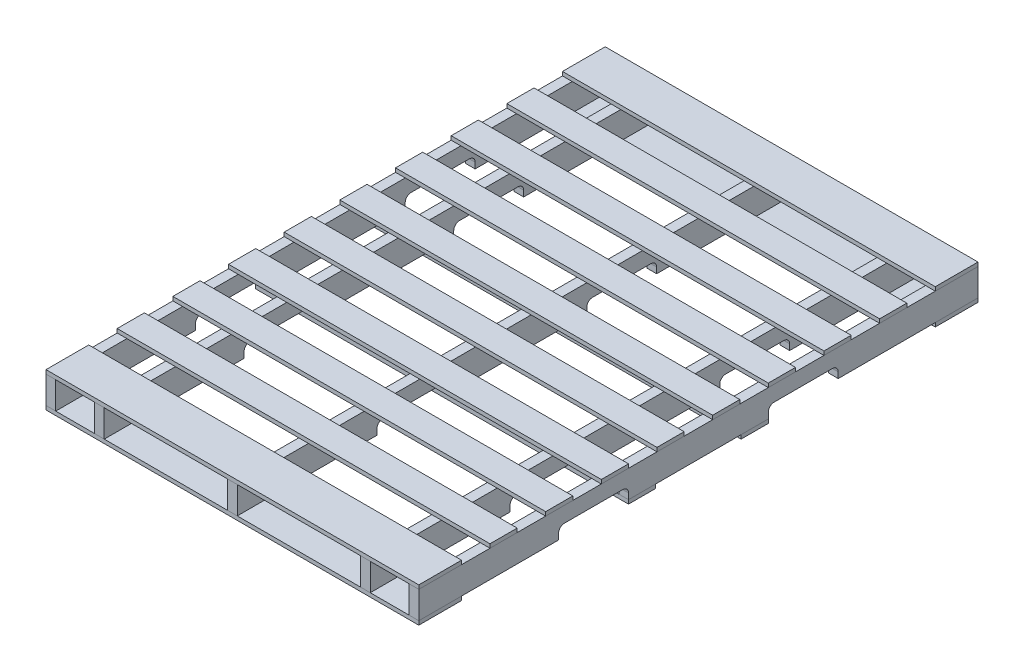
SolidWorks part; units mm, degrees
ref_plane "Front Plane" through (0, 0, 0) normal (0, 0, 1) x (1, 0, 0)
ref_plane "Top Plane" through (0, 0, 0) normal (0, 1, 0) x (1, 0, 0)
ref_plane "Right Plane" through (0, 0, 0) normal (1, 0, 0) x (0, 0, -1)
sketch "Sketch1" plane through (0, 0, 0) normal (0, 0, 1) x (1, 0, 0)
  line L0 (-609.6, 0) -> (609.6, 0) construction
  line L5 (-609.6, 57.15) -> (-609.6, -57.15) construction
  line L6 (609.6, 57.15) -> (609.6, -57.15) construction
  line L11 (-609.6, -57.15) -> (609.6, -57.15) construction
  line L12 (-609.6, 57.15) -> (609.6, 57.15) construction
  line L13 (-577.85, 57.15) -> (-577.85, -57.15) construction
  line L15 (-450.85, 57.15) -> (-450.85, -57.15) construction
  line L16 (-419.1, -57.15) -> (-419.1, 57.15) construction
  line L17 (0, 57.15) -> (0, -57.15) construction
  line L18 (-609.6, 0) -> (-577.85, 0)
  line L19 (-450.85, 0) -> (-419.1, 0)
  line L21 (577.85, 57.15) -> (577.85, -57.15) construction
  line L22 (-609.6, 44.45) -> (609.6, 44.45) construction
  line L23 (-609.6, -44.45) -> (609.6, -44.45) construction
  line L24 (419.1, 57.15) -> (450.85, 57.15)
  line L25 (419.1, 57.15) -> (419.1, -57.15)
  line L26 (419.1, -57.15) -> (450.85, -57.15)
  line L27 (450.85, 57.15) -> (450.85, -57.15)
  line L28 (-15.875, -57.15) -> (15.875, -57.15)
  line L29 (-15.875, -57.15) -> (-15.875, 57.15)
  line L30 (-15.875, 57.15) -> (15.875, 57.15)
  line L31 (15.875, -57.15) -> (15.875, 57.15)
  line L32 (-15.875, -57.15) -> (15.875, 57.15) construction
  line L33 (-15.875, 57.15) -> (15.875, -57.15) construction
  point P3 (0, 0)
  point P6 (-609.6, 0)
  point P9 (609.6, 0)
  point P23 (0, 0)
  point P32 (0, 0)
  dimension "D1" = 31.75
  dimension "Width" = 1219.2
  dimension "Height" = 114.3
  dimension "Maximum Fork Width" = 403.225
  dimension "D3" = 12.7
  dimension "Maximum Fork Height" = 88.9
sketch "Sketch2" plane through (0, 0, 0) normal (1, 0, 0) x (0, 0, -1)
  line L0 (914.4, 0) -> (-914.4, 0) construction
  point P4 (0, 0)
  dimension "Depth" = 1828.8
sketch "Sketch3" plane through (0, 0, 0) normal (0, 0, 1) x (1, 0, 0)
  line L0 (577.85, 57.15) -> (577.85, -57.15) construction
  line L5 (450.85, 57.15) -> (450.85, -57.15) construction
  line L6 (-577.85, 57.15) -> (-577.85, -57.15) construction
  line L7 (-609.6, 44.45) -> (-577.85, 44.45)
  line L8 (-609.6, 44.45) -> (-609.6, -44.45)
  line L9 (-609.6, -44.45) -> (-577.85, -44.45)
  line L10 (-577.85, 44.45) -> (-577.85, -44.45)
  line L11 (-609.6, 44.45) -> (609.6, 44.45) construction
  line L12 (450.85, 44.45) -> (419.1, 44.45)
  line L13 (-609.6, -44.45) -> (609.6, -44.45) construction
  line L14 (577.85, 44.45) -> (609.6, 44.45)
  line L15 (577.85, 44.45) -> (577.85, -44.45)
  line L16 (577.85, -44.45) -> (609.6, -44.45)
  line L17 (609.6, 44.45) -> (609.6, -44.45)
  line L18 (-609.6, 57.15) -> (-609.6, -57.15) construction
  line L19 (450.85, 44.45) -> (450.85, -44.45)
  line L20 (-450.85, 57.15) -> (-450.85, -57.15) construction
  line L21 (-450.85, 44.45) -> (-419.1, 44.45)
  line L22 (-450.85, 44.45) -> (-450.85, -44.45)
  line L23 (-450.85, -44.45) -> (-419.1, -44.45)
  line L24 (-419.1, 44.45) -> (-419.1, -44.45)
  line L25 (-419.1, -57.15) -> (-419.1, 57.15) construction
  line L26 (450.85, -44.45) -> (419.1, -44.45)
  line L27 (419.1, 44.45) -> (419.1, -44.45)
  line L28 (419.1, 57.15) -> (419.1, -57.15) construction
  line L29 (15.875, -57.15) -> (15.875, 57.15) construction
  line L30 (-15.875, -44.45) -> (15.875, -44.45)
  line L31 (-15.875, -44.45) -> (-15.875, 44.45)
  line L32 (-15.875, 44.45) -> (15.875, 44.45)
  line L33 (15.875, -44.45) -> (15.875, 44.45)
  line L34 (-15.875, -44.45) -> (15.875, 44.45) construction
  line L35 (-15.875, 44.45) -> (15.875, -44.45) construction
  point P35 (0, 0)
extrude "Boss-Extrude1" add sketch "Sketch3" along normal up to vertex (914.4 mm away) and the other way up to vertex (914.4 mm away) up to point (0, 0, 914.4) other way up to point (0, 0, -914.4)
sketch "Sketch4" plane through (0, 44.45, 0) normal (0, 1, 0) x (1, 0, 0)
  line L0 (609.6, -914.4) -> (609.6, 914.4) construction
  line L1 (-609.6, -914.4) -> (609.6, -914.4)
  line L2 (-609.6, -914.4) -> (-609.6, -774.7)
  line L3 (-609.6, -774.7) -> (609.6, -774.7)
  line L4 (609.6, -914.4) -> (609.6, -774.7)
  line L22 (-609.6, -914.4) -> (-609.6, 914.4) construction
  line L26 (-609.6, 774.7) -> (609.6, 774.7)
  line L27 (-609.6, 774.7) -> (-609.6, 914.4)
  line L28 (-609.6, 914.4) -> (609.6, 914.4)
  line L29 (609.6, 774.7) -> (609.6, 914.4)
  line L30 (609.6, 592.6667) -> (609.6, 499.5333) construction
  line L31 (-609.6, -681.5667) -> (609.6, -681.5667)
  line L32 (-609.6, -681.5667) -> (-609.6, -592.6667)
  line L33 (-609.6, -592.6667) -> (609.6, -592.6667)
  line L34 (609.6, -681.5667) -> (609.6, -592.6667)
  line L35 (-609.6, -499.5333) -> (609.6, -499.5333)
  line L36 (-609.6, -499.5333) -> (-609.6, -410.6333)
  line L37 (-609.6, -410.6333) -> (609.6, -410.6333)
  line L38 (609.6, -499.5333) -> (609.6, -410.6333)
  line L39 (-609.6, 681.5667) -> (609.6, 681.5667)
  line L40 (-609.6, 681.5667) -> (-609.6, 592.6667)
  line L41 (-609.6, 592.6667) -> (609.6, 592.6667)
  line L42 (609.6, 681.5667) -> (609.6, 592.6667)
  line L43 (-609.6, -46.5667) -> (609.6, -46.5667)
  line L44 (-609.6, -46.5667) -> (-609.6, -135.4667)
  line L45 (-609.6, -135.4667) -> (609.6, -135.4667)
  line L46 (609.6, -46.5667) -> (609.6, -135.4667)
  line L47 (-609.6, -228.6) -> (609.6, -228.6)
  line L48 (-609.6, -228.6) -> (-609.6, -317.5)
  line L49 (-609.6, -317.5) -> (609.6, -317.5)
  line L50 (609.6, -228.6) -> (609.6, -317.5)
  line L51 (609.6, 499.5333) -> (-609.6, 499.5333)
  line L52 (609.6, 499.5333) -> (609.6, 410.6333)
  line L53 (609.6, 410.6333) -> (-609.6, 410.6333)
  line L54 (-609.6, 499.5333) -> (-609.6, 410.6333)
  line L55 (609.6, 317.5) -> (-609.6, 317.5)
  line L56 (609.6, 317.5) -> (609.6, 228.6)
  line L57 (609.6, 228.6) -> (-609.6, 228.6)
  line L58 (-609.6, 317.5) -> (-609.6, 228.6)
  line L59 (609.6, 135.4667) -> (-609.6, 135.4667)
  line L60 (609.6, 135.4667) -> (609.6, 46.5667)
  line L61 (609.6, 46.5667) -> (-609.6, 46.5667)
  line L62 (-609.6, 135.4667) -> (-609.6, 46.5667)
  line L63 (609.6, 774.7) -> (609.6, 681.5667) construction
  line L64 (609.6, 410.6333) -> (609.6, 317.5) construction
  line L65 (609.6, 228.6) -> (609.6, 135.4667) construction
  line L66 (609.6, 46.5667) -> (609.6, -46.5667) construction
  line L67 (609.6, -135.4667) -> (609.6, -228.6) construction
  line L68 (609.6, -317.5) -> (609.6, -410.6333) construction
  line L69 (609.6, -499.5333) -> (609.6, -592.6667) construction
  line L70 (609.6, -681.5667) -> (609.6, -774.7) construction
  line L71 (609.6, 681.5667) -> (609.6, 774.7) construction
  dimension "D1" = 139.7
  dimension "D3" = 88.9
extrude "Boss-Extrude2" add sketch "Sketch4" along normal up to vertex (12.7 mm away) separate body up to point (-609.6, 57.15, 0)
sketch "Sketch5" plane through (0, -44.45, 0) normal (0, -1, 0) x (1, 0, 0)
  line L0 (609.6, 914.4) -> (609.6, -914.4) construction
  line L1 (-609.6, 914.4) -> (609.6, 914.4)
  line L2 (-609.6, 914.4) -> (-609.6, 774.7)
  line L3 (-609.6, 774.7) -> (609.6, 774.7)
  line L4 (609.6, 914.4) -> (609.6, 774.7)
  line L5 (-609.6, -914.4) -> (609.6, -914.4)
  line L6 (-609.6, -914.4) -> (-609.6, -774.7)
  line L7 (-609.6, -774.7) -> (609.6, -774.7)
  line L8 (609.6, -914.4) -> (609.6, -774.7)
  line L15 (-609.6, 914.4) -> (-609.6, -914.4) construction
  line L16 (-609.6, 914.4) -> (-609.6, 774.7) construction
  line L17 (609.6, 914.4) -> (609.6, 774.7) construction
  line L18 (-609.6, 228.6) -> (609.6, 228.6)
  line L19 (-609.6, 228.6) -> (-609.6, 139.7)
  line L20 (-609.6, 139.7) -> (609.6, 139.7)
  line L21 (609.6, 228.6) -> (609.6, 139.7)
  line L22 (-609.6, -228.6) -> (609.6, -228.6)
  line L23 (-609.6, -228.6) -> (-609.6, -139.7)
  line L24 (-609.6, -139.7) -> (609.6, -139.7)
  line L25 (609.6, -228.6) -> (609.6, -139.7)
  dimension "D1" = 546.1
  dimension "D2" = 546.1
  dimension "D3" = 88.9
  dimension "D4" = 139.7
extrude "Boss-Extrude3" add sketch "Sketch5" along normal up to vertex (12.7 mm away) separate body up to point (-609.6, -57.15, 0)
sketch "Sketch8" plane through (609.6, 0, 0) normal (1, 0, 0) x (0, 0, -1)
  line L1 (-228.6, -44.45) -> (-457.2, -44.45)
  line L2 (-228.6, -44.45) -> (-228.6, -25.4)
  line L3 (-247.65, -6.35) -> (-438.15, -6.35)
  line L4 (-457.2, -44.45) -> (-457.2, -25.4)
  line L5 (228.6, -44.45) -> (457.2, -44.45)
  line L6 (228.6, -44.45) -> (228.6, -25.4)
  line L7 (247.65, -6.35) -> (438.15, -6.35)
  line L8 (457.2, -44.45) -> (457.2, -25.4)
  arc A0 (438.15, -6.35) -> (457.2, -25.4) centre (438.15, -25.4) cw
  arc A1 (228.6, -25.4) -> (247.65, -6.35) centre (247.65, -25.4) cw
  arc A2 (-228.6, -25.4) -> (-247.65, -6.35) centre (-247.65, -25.4) ccw
  arc A3 (-438.15, -6.35) -> (-457.2, -25.4) centre (-438.15, -25.4) ccw
  point P18 (-457.2, -6.35)
  dimension "D3" = 19.05
  dimension "D1" = 38.1
  dimension "D2" = 228.6
extrude "Cut-Extrude2" cut sketch "Sketch8" against normal through all both and the other way through all
sketch "Sketch7" plane through (0, 0, 0) normal (0, 1, 0) x (1, 0, 0)
  line L0 (0, 914.4) -> (609.6, 914.4) construction
  line L2 (609.6, 914.4) -> (609.6, 0) construction
  line L3 (609.6, 0) -> (609.6, -914.4) construction
  line L4 (609.6, -914.4) -> (0, -914.4) construction
  line L5 (-609.6, -914.4) -> (609.6, -914.4) construction
  line L6 (-609.6, 914.4) -> (0, 914.4) construction
